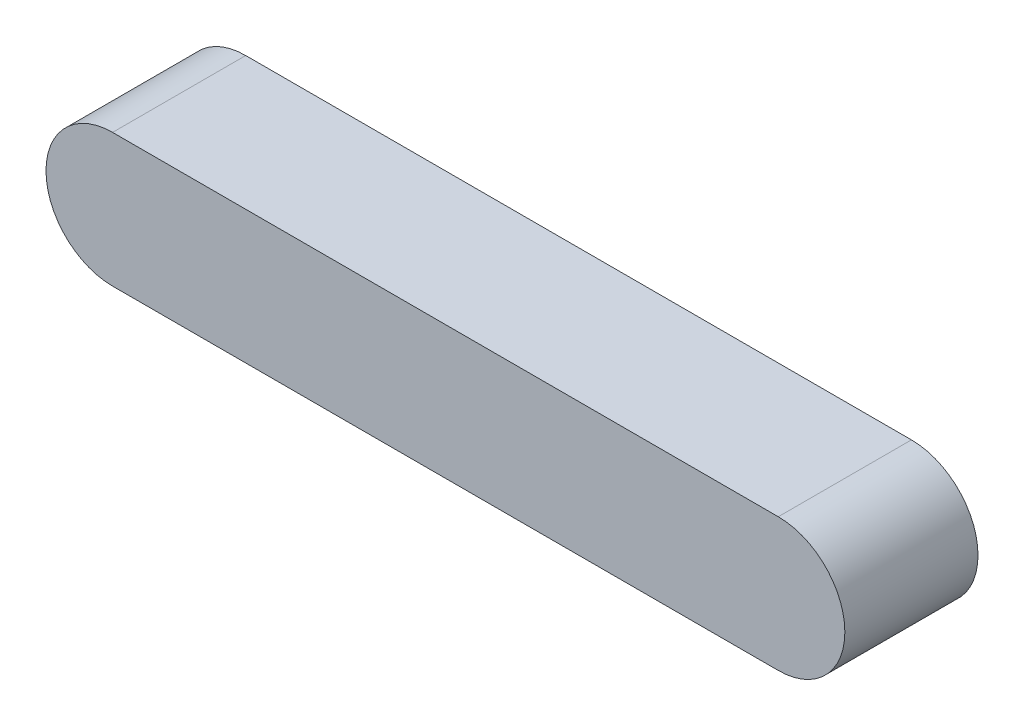
SolidWorks part; units mm, degrees
ref_plane "Plan de face" through (0, 0, 0) normal (0, 0, 1) x (1, 0, 0)
ref_plane "Plan de dessus" through (0, 0, 0) normal (0, 1, 0) x (1, 0, 0)
ref_plane "Plan de droite" through (0, 0, 0) normal (1, 0, 0) x (0, 0, -1)
sketch "Esquisse1" plane through (0, 0, 0) normal (0, 0, 1) x (1, 0, 0)
  line L0 (0, 0) -> (10, 0)
  line L1 (10, -2) -> (0, -2)
  arc A0 (10, 0) -> (10, -2) centre (10, -1) cw
  arc A1 (0, -2) -> (0, 0) centre (0, -1) cw
  dimension "D1" = 2
  dimension "D2" = 10
extrude "Extrusion1" add sketch "Esquisse1" along normal blind 2
